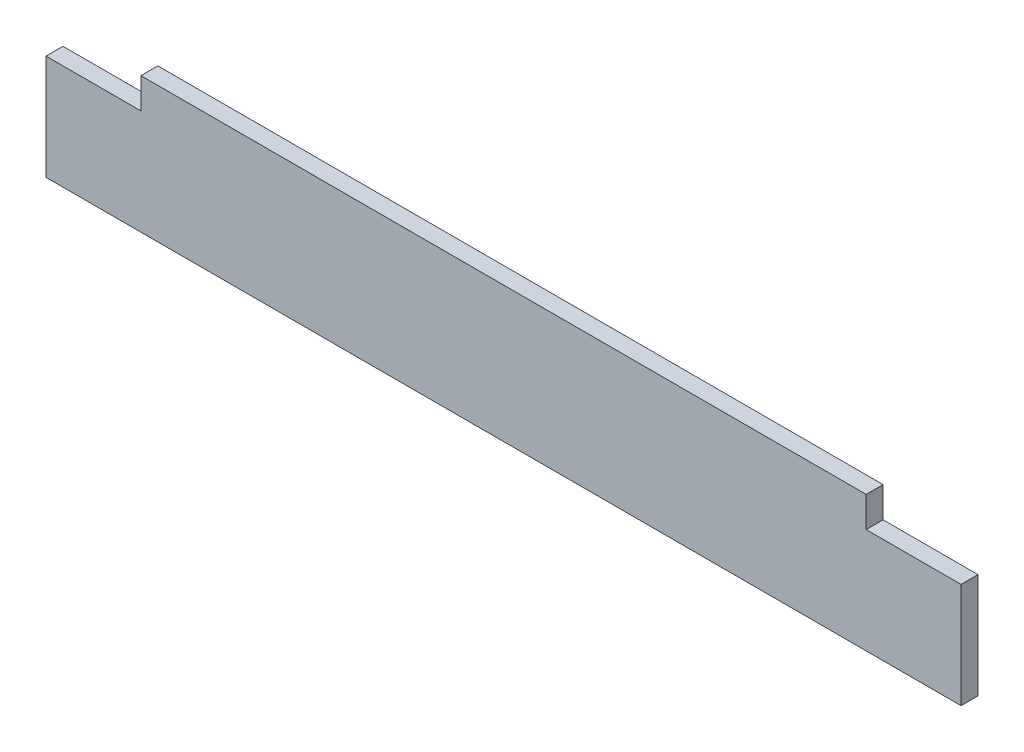
SolidWorks part; units mm, degrees
ref_plane "Plan de face" through (0, 0, 0) normal (0, 0, 1) x (1, 0, 0)
ref_plane "Plan de dessus" through (0, 0, 0) normal (0, 1, 0) x (1, 0, 0)
ref_plane "Plan de droite" through (0, 0, 0) normal (1, 0, 0) x (0, 0, -1)
sketch "Esquisse1" plane through (0, 0, 0) normal (0, 0, 1) x (1, 0, 0)
  line L1 (-135, 20) -> (135, 20)
  line L2 (-135, 20) -> (-135, -20)
  line L3 (-135, -20) -> (135, -20)
  line L4 (135, 20) -> (135, -20)
  line L5 (-135, 20) -> (135, -20) construction
  line L6 (-135, -20) -> (135, 20) construction
  point P0 (0, 0)
  dimension "D1" = 40
  dimension "D2" = 270
extrude "Boss.-Extru.1" add sketch "Esquisse1" along normal blind 5
sketch "Esquisse2" plane through (0, 20, 0) normal (0, 1, 0) x (1, 0, 0)
  line L0 (135, -5) -> (-135, -5) construction
  line L1 (135, 0) -> (107, 0)
  line L2 (135, 0) -> (135, -5)
  line L3 (135, -5) -> (107, -5)
  line L4 (107, 0) -> (107, -5)
  line L6 (-135, 0) -> (-107, 0)
  line L7 (-135, 0) -> (-135, -5)
  line L8 (-135, -5) -> (-107, -5)
  line L9 (-107, 0) -> (-107, -5)
  dimension "D1" = 28
  dimension "D2" = 28
extrude "Enlèv. mat.-Extru.1" cut sketch "Esquisse2" against normal blind 9
